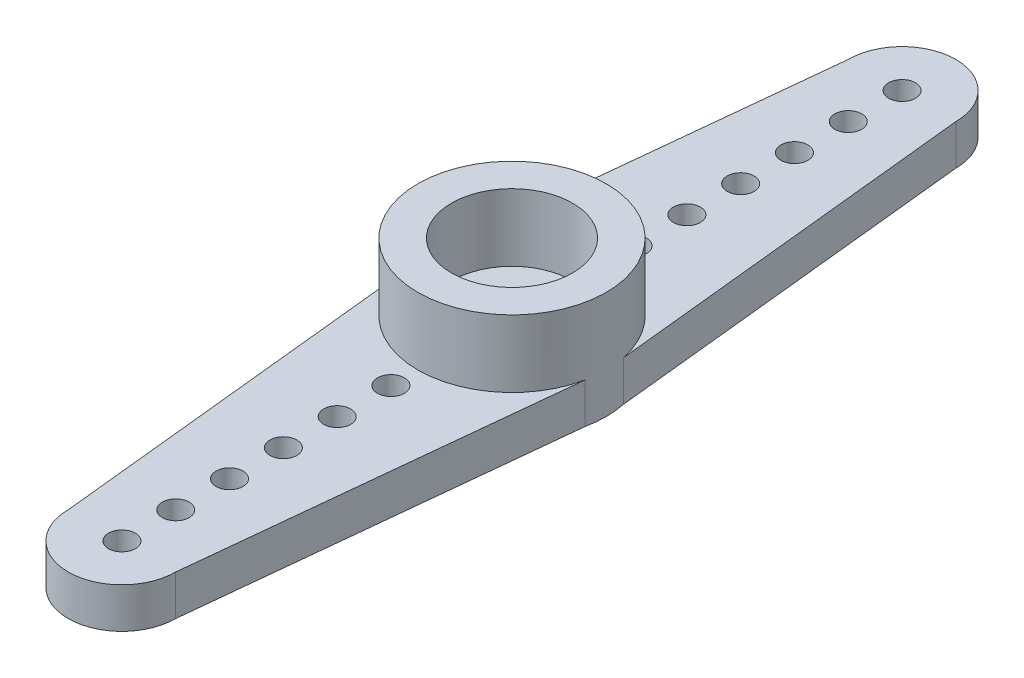
SolidWorks part; units mm, degrees
ref_plane "Alzado" through (0, 0, 0) normal (0, 0, 1) x (1, 0, 0)
ref_plane "Planta" through (0, 0, 0) normal (0, 1, 0) x (1, 0, 0)
ref_plane "Vista lateral" through (0, 0, 0) normal (1, 0, 0) x (0, 0, -1)
sketch "Croquis1" plane through (0, 0, 0) normal (0, 1, 0) x (1, 0, 0)
  line L0 (0, 0) -> (0, -10.5) construction
  line L1 (0, 0) -> (0, 14.5) construction
  line L2 (-3.5, 0) -> (-2, -14.5) construction
  line L3 (2, -14.5) -> (3.5, 0) construction
  line L4 (-3.4259, -0.7165) -> (-2, -14.5)
  line L5 (3.4259, -0.7165) -> (2, -14.5)
  line L6 (-2, 14.5) -> (-3.4259, 0.7165)
  line L7 (2, 14.5) -> (3.4259, 0.7165)
  arc A0 (-3.4259, 0.7165) -> (-3.4259, -0.7165) centre (0, 0) ccw
  arc A1 (-2, -14.5) -> (2, -14.5) centre (0, -14.5) ccw
  circle A2 centre (0, -14.5) radius 0.5
  circle A3 centre (0, -12.5) radius 0.5
  circle A4 centre (0, -10.5) radius 0.5
  circle A5 centre (0, -8.5) radius 0.5
  circle A6 centre (0, -6.5) radius 0.5
  circle A7 centre (0, -4.5) radius 0.5
  arc A8 (2, 14.5) -> (-2, 14.5) centre (0, 14.5) ccw
  circle A9 centre (0, 14.5) radius 0.5
  circle A10 centre (0, 12.5) radius 0.5
  circle A11 centre (0, 10.5) radius 0.5
  circle A12 centre (0, 8.5) radius 0.5
  circle A13 centre (0, 6.5) radius 0.5
  circle A14 centre (0, 4.5) radius 0.5
  arc A15 (3.4259, -0.7165) -> (3.4259, 0.7165) centre (0, 0) ccw
  dimension "D1" = 6
  dimension "D2" = 6
extrude "Saliente-Extruir1" add sketch "Croquis1" along normal blind 1.5
sketch "Croquis2" plane through (0, 1.5, 0) normal (0, 1, 0) x (1, 0, 0)
  circle A0 centre (0, 0) radius 2.25
  circle A1 centre (0, 0) radius 3.5
extrude "Saliente-Extruir2" add sketch "Croquis2" along normal blind 2.5
sketch "Croquis3" plane through (0, 0, 0) normal (0, -1, 0) x (1, 0, 0)
  circle A0 centre (0, 0) radius 2.5
extrude "Cortar-Extruir1" cut sketch "Croquis3" against normal blind 1
sketch "Croquis4" plane through (0, 1.5, 0) normal (0, 1, 0) x (1, 0, 0)
  circle A0 centre (0, 0) radius 1
extrude "Cortar-Extruir2" cut sketch "Croquis4" along direction (0, -1, 0) on the side against the normal blind 1
